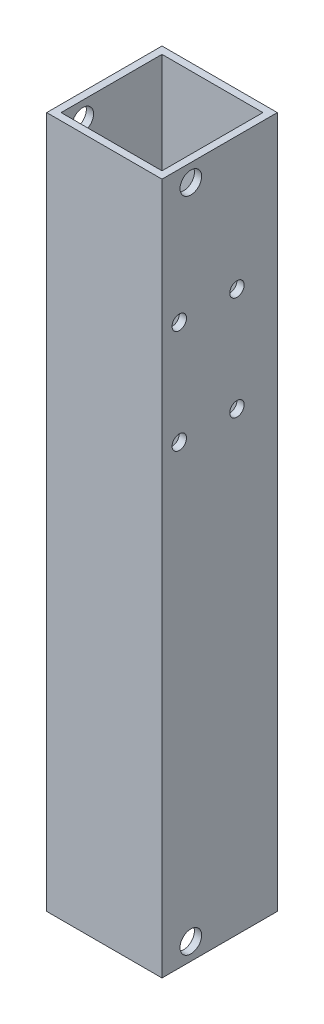
SolidWorks part; units mm, degrees
material "6061-O (SS)"
ref_plane "Front Plane" through (0, 0, 0) normal (0, 0, 1) x (1, 0, 0)
ref_plane "Top Plane" through (0, 0, 0) normal (0, 1, 0) x (1, 0, 0)
ref_plane "Right Plane" through (0, 0, 0) normal (1, 0, 0) x (0, 0, -1)
sketch "Sketch1" plane through (0, 0, 0) normal (0, 0, 1) x (1, 0, 0)
  line L1 (63.386, -24.9496) -> (88.786, -24.9496)
  line L2 (63.386, -24.9496) -> (63.386, -177.3496)
  line L3 (63.386, -177.3496) -> (88.786, -177.3496)
  line L4 (88.786, -24.9496) -> (88.786, -177.3496)
  dimension "D1" = 152.4
  dimension "D2" = 25.4
extrude "Boss-Extrude1" add sketch "Sketch1" along normal blind 25.4
sketch "Sketch2" plane through (0, -24.9496, 0) normal (0, 1, 0) x (1, 0, 0)
  line L0 (63.386, -25.4) -> (63.386, 0) construction
  line L1 (64.9735, -23.8125) -> (87.1985, -23.8125)
  line L2 (64.9735, -23.8125) -> (64.9735, -1.5875)
  line L3 (64.9735, -1.5875) -> (87.1985, -1.5875)
  line L4 (87.1985, -23.8125) -> (87.1985, -1.5875)
  line L5 (88.786, -25.4) -> (88.786, 0) construction
  line L6 (88.786, -25.4) -> (63.386, -25.4) construction
  line L7 (88.786, 0) -> (63.386, 0) construction
  dimension "D1" = 1.5875
  dimension "D2" = 1.5875
  dimension "D3" = 1.5875
  dimension "D4" = 1.5875
extrude "Cut-Extrude1" cut sketch "Sketch2" against normal blind 279.4
sketch "Sketch3" plane through (88.786, 0, 0) normal (1, 0, 0) x (0, 0, -1)
  line L0 (-25.4, -24.9496) -> (0, -24.9496) construction
  line L1 (-25.4, -177.3496) -> (-25.4, -24.9496) construction
  line L2 (-36.9478, -101.1496) -> (27.4157, -101.1496) construction
  line L4 (-25.4, -177.3496) -> (0, -177.3496) construction
  point P1 (-19.05, -28.7596)
  point P10 (-19.05, -173.5396)
  point P12 (-21.59, -54.1596)
  point P13 (-21.59, -77.0196)
  point P14 (-8.89, -54.1596)
  point P15 (-8.89, -77.0196)
  dimension "D1" = 29.21
  dimension "D2" = 3.81
  dimension "D3" = 29.21
  dimension "D4" = 6.35
  dimension "D5" = 76.2
  dimension "D6" = 3.81
  dimension "D7" = 3.81
  dimension "D8" = 12.7
  dimension "D9" = 12.7
  dimension "D10" = 22.86
  dimension "D11" = 22.86
hole_wizard "3/16 (0.1875) Diameter Hole2" positions "Sketch6" profile "Sketch7" hole size "3/16" standard "ANSI Inch" end condition through all
sketch "Sketch6" plane through (88.786, 0, 0) normal (1, 0, 0) x (0, 0, -1)
  point P0 (-19.05, -173.5396)
  point P3 (-19.05, -28.7596)
sketch "Sketch7" plane through (88.786, -173.5396, 19.05) normal (0, 1, 0) x (0, 0, -1)
  line L0 (0, 0) -> (0, 25.4)
  line L1 (0, 25.4) -> (2.3812, 25.4)
  line L2 (2.3812, 25.4) -> (2.3812, 0)
  line L5 (2.3812, 0) -> (0, 0)
  line L11 (0, -6.35) -> (0, 107.95) construction
  dimension "Thru Hole Dia." = 4.7625
  dimension "Thru Hole Depth" = 25.4
hole_wizard "1/8 (0.125) Diameter Hole1" positions "Sketch8" profile "Sketch9" hole size "1/8" standard "ANSI Inch" end condition through all
sketch "Sketch8" plane through (88.786, 0, 0) normal (1, 0, 0) x (0, 0, -1)
  point P0 (-21.59, -77.0196)
  point P3 (-8.89, -77.0196)
  point P6 (-21.59, -54.1596)
  point P9 (-8.89, -54.1596)
sketch "Sketch9" plane through (88.786, -77.0196, 21.59) normal (0, 1, 0) x (0, 0, -1)
  line L0 (0, 0) -> (0, 25.4)
  line L1 (0, 25.4) -> (1.5875, 25.4)
  line L2 (1.5875, 25.4) -> (1.5875, 0)
  line L5 (1.5875, 0) -> (0, 0)
  line L11 (0, -6.35) -> (0, 107.95) construction
  dimension "Thru Hole Dia." = 3.175
  dimension "Thru Hole Depth" = 25.4
